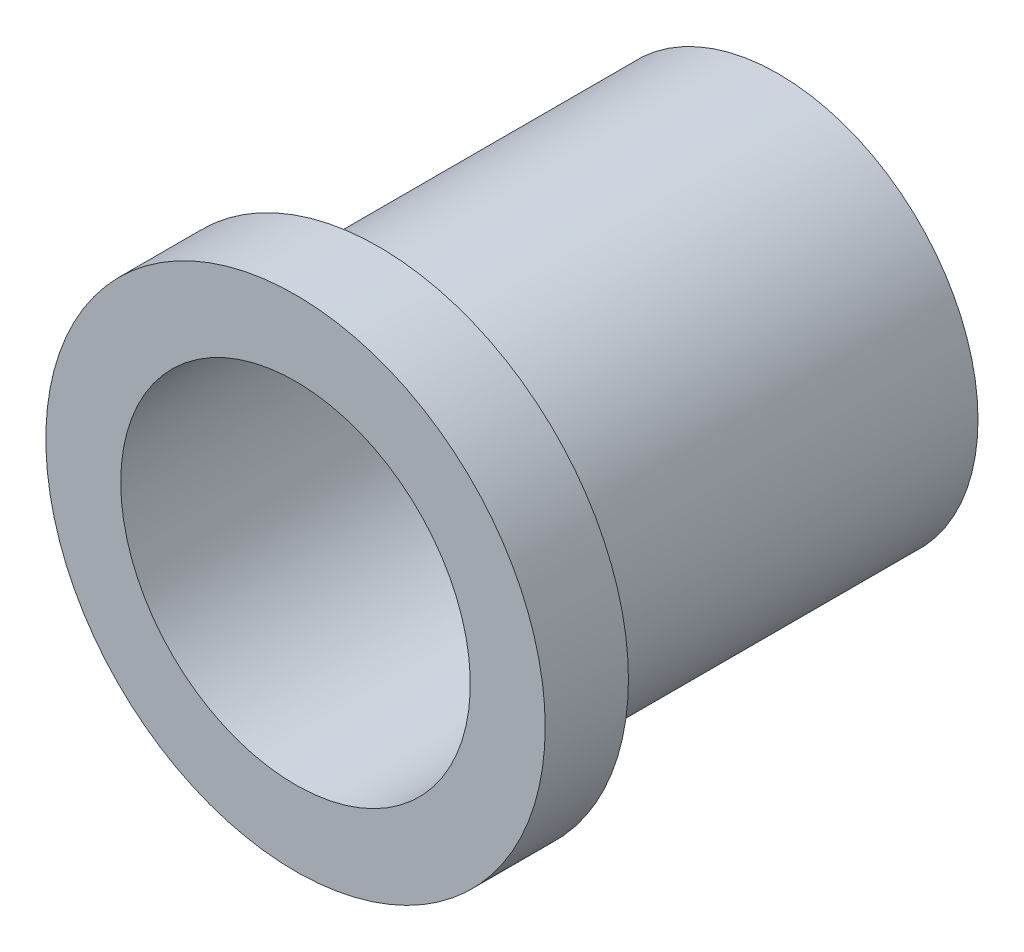
SolidWorks part; units mm, degrees
ref_plane "Front Plane" through (0, 0, 0) normal (0, 0, 1) x (1, 0, 0)
ref_plane "Top Plane" through (0, 0, 0) normal (0, 1, 0) x (1, 0, 0)
ref_plane "Right Plane" through (0, 0, 0) normal (1, 0, 0) x (0, 0, -1)
sketch "Sketch1" plane through (0, 0, 0) normal (0, 0, 1) x (1, 0, 0)
  line L0 (25.6069, 0) -> (0, 0) construction
  line L1 (0, 0) -> (0, 18.1067) construction
  circle A0 centre (0, 0) radius 12
  dimension "D1" = 24
extrude "Boss-Extrude1" add sketch "Sketch1" along normal blind 24
sketch "Sketch2" plane through (0, 0, 24) normal (0, 0, 1) x (1, 0, 0)
  circle A0 centre (0, 0) radius 15
  dimension "D1" = 30
extrude "Boss-Extrude2" add sketch "Sketch2" along normal blind 5
sketch "Sketch3" plane through (0, 0, 0) normal (0, 0, -1) x (-1, 0, 0)
  circle A0 centre (0, 0) radius 10.5
  dimension "D1" = 21
extrude "Cut-Extrude2" cut sketch "Sketch3" against normal through all
